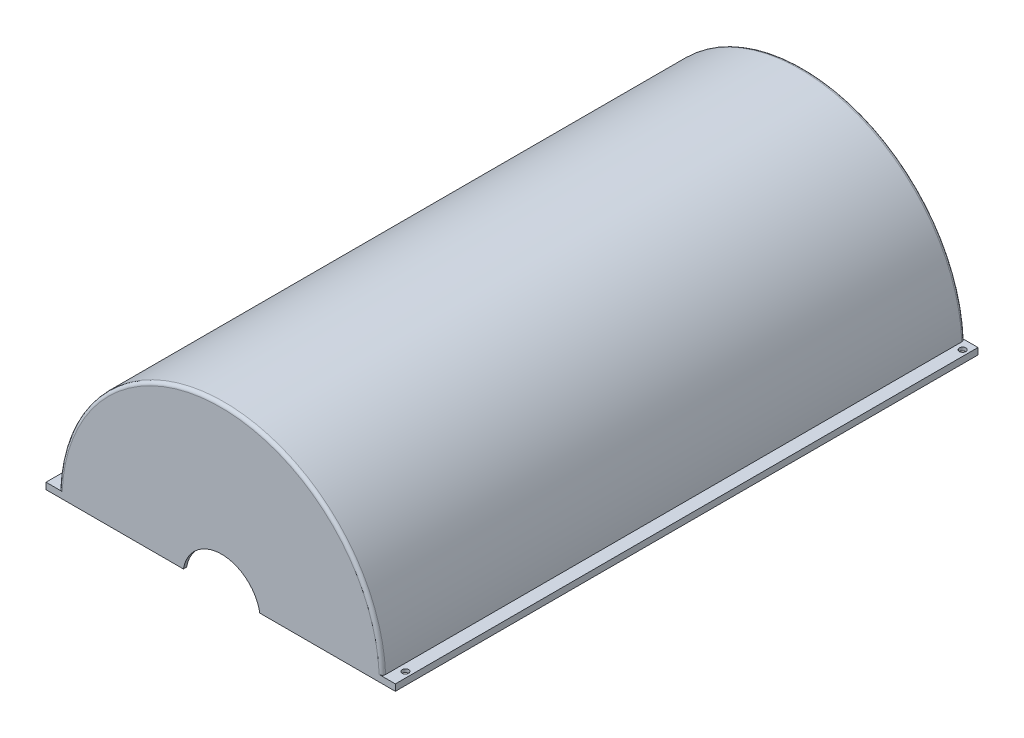
SolidWorks part; units mm, degrees
ref_plane "Front Plane" through (0, 0, 0) normal (0, 0, 1) x (1, 0, 0)
ref_plane "Top Plane" through (0, 0, 0) normal (0, 1, 0) x (1, 0, 0)
ref_plane "Right Plane" through (0, 0, 0) normal (1, 0, 0) x (0, 0, -1)
sketch "Sketch1" plane through (0, 0, 0) normal (0, 0, 1) x (1, 0, 0)
  line L0 (0, 0) -> (384.7575, 0)
  line L1 (620.9318, 0) -> (1000, 0)
  arc A0 (1000, 0) -> (0, 0) centre (500, 0) ccw
  arc A1 (384.7575, 0) -> (620.9318, 0) centre (502.8446, -21.3409) cw
  point P7 (622.8446, -0.1413)
  dimension "D2" = 120
  dimension "D1" = 1000
extrude "Boss-Extrude1" add sketch "Sketch1" along normal blind 1800
sketch "Sketch2" plane through (0, 0, 0) normal (0, 0, 1) x (1, 0, 0)
  line L0 (1000, 0) -> (1039.5998, 0)
  line L1 (1039.5998, 0) -> (1039.5998, 20)
  line L2 (1039.5998, 20) -> (999.5998, 20)
  line L3 (0, 0) -> (-39.5998, 0)
  line L4 (-39.5998, 0) -> (-39.5998, 20)
  line L5 (-39.5998, 20) -> (0.4002, 20)
  line L6 (999.5998, 20) -> (1000, 0)
  line L7 (0.4002, 20) -> (0, 0)
  arc A0 (1000, 0) -> (0, 0) centre (500, 0) ccw construction
extrude "Boss-Extrude2" add sketch "Sketch2" along normal blind 1800
shell "Shell1" thickness 10
fillet "Fillet1" radius 10 2 edges at (500, 500, 1800) (500, 500, 0)
sketch "Sketch3" plane through (0, 20, 0) normal (0, 1, 0) x (1, 0, 0)
  circle A0 centre (-18.2357, -19.6895) radius 10
  circle A1 centre (1021.8175, -29.6895) radius 10
  circle A2 centre (1021.8175, -1751.2087) radius 10
  circle A3 centre (-18.2357, -1741.2087) radius 10
extrude "Cut-Extrude1" cut sketch "Sketch3" against normal through all
